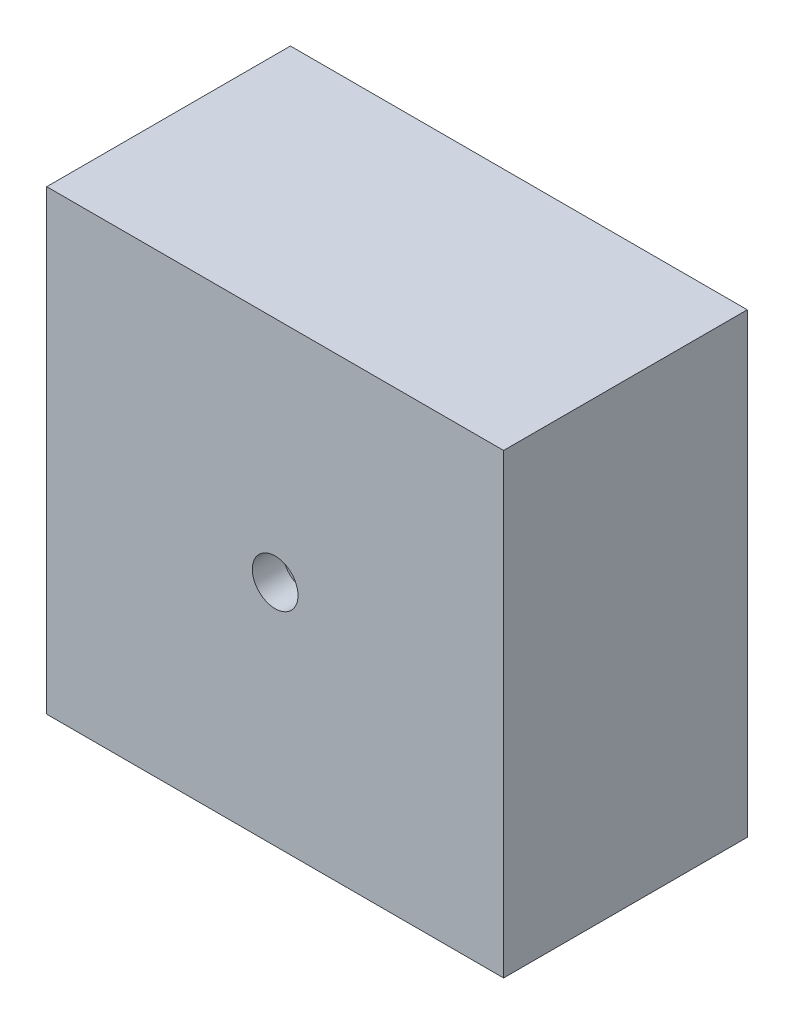
SolidWorks part; units mm, degrees
material "Custom Plastic"
ref_plane "Front Plane" through (0, 0, 0) normal (0, 0, 1) x (1, 0, 0)
ref_plane "Top Plane" through (0, 0, 0) normal (0, 1, 0) x (1, 0, 0)
ref_plane "Right Plane" through (0, 0, 0) normal (1, 0, 0) x (0, 0, -1)
other "Configuration Table"
sketch "Sketch1" plane through (0, 0, 0) normal (0, 0, 1) x (1, 0, 0)
  circle A0 centre (0, 0) radius 10
  dimension "D1" = 20
extrude "Boss-Extrude1" add sketch "Sketch1" along normal mid plane 10
sketch "Sketch2" plane through (0, 0, 0) normal (0, 0, 1) x (1, 0, 0)
  line L1 (-15, -15) -> (15, -15)
  line L2 (-15, -15) -> (-15, 15)
  line L3 (-15, 15) -> (15, 15)
  line L4 (15, -15) -> (15, 15)
  line L5 (-15, -15) -> (15, 15) construction
  line L6 (-15, 15) -> (15, -15) construction
  circle A0 centre (0, 0) radius 12
  dimension "D1" = 24
  dimension "D2" = 30
extrude "Boss-Extrude2" add sketch "Sketch2" along normal mid plane 12 separate body
sketch "Sketch3" plane through (0, 0, 6) normal (0, 0, 1) x (1, 0, 0)
  line L4 (15, -15) -> (15, 15)
  line L5 (15, 15) -> (-15, 15)
  line L6 (-15, 15) -> (-15, -15)
  line L7 (-15, -15) -> (15, -15)
  line L8 (15, -15) -> (15, 15)
  line L9 (15, 15) -> (-15, 15)
  line L10 (-15, 15) -> (-15, -15)
  line L11 (-15, -15) -> (15, -15)
  dimension "D1" = 0
extrude "Boss-Extrude3" add sketch "Sketch3" along normal blind 2
mirror "Mirror1" about plane through (0, 0, 0) normal (0, 0, 1) of "Boss-Extrude3"
sketch "Sketch4" plane through (0, 0, 8) normal (0, 0, 1) x (1, 0, 0)
  circle A0 centre (0, 0) radius 1.5
  dimension "D1" = 3
extrude "Cut-Extrude1" cut sketch "Sketch4" against normal through all
